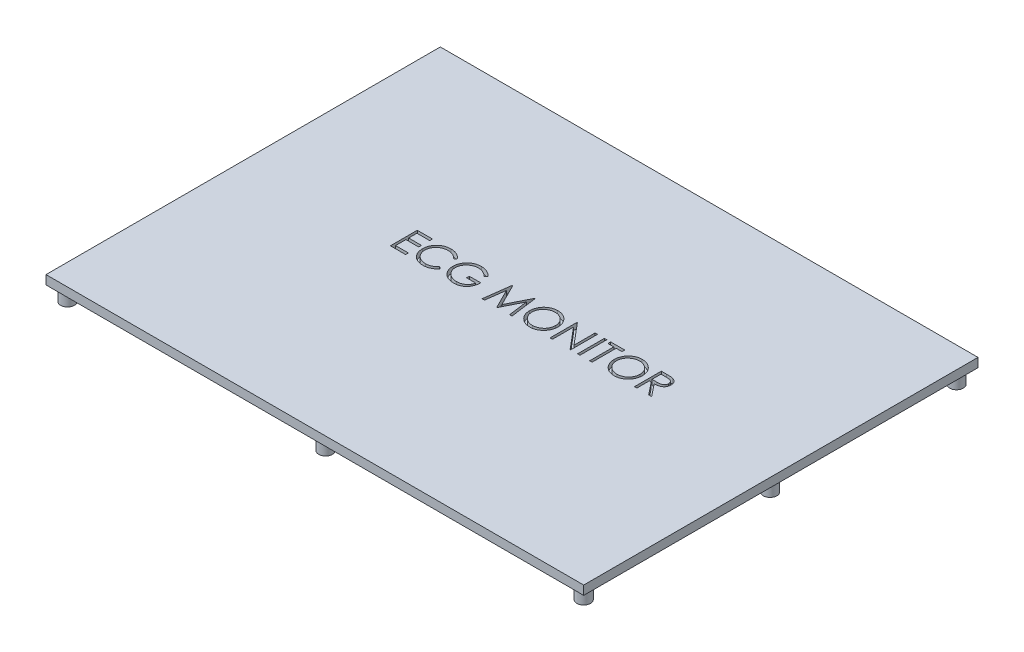
SolidWorks part; units mm, degrees
ref_plane "Front Plane" through (0, 0, 0) normal (0, 0, 1) x (1, 0, 0)
ref_plane "Top Plane" through (0, 0, 0) normal (0, 1, 0) x (1, 0, 0)
ref_plane "Right Plane" through (0, 0, 0) normal (1, 0, 0) x (0, 0, -1)
sketch "Sketch1" plane through (0, 0, 0) normal (0, 1, 0) x (1, 0, 0)
  line L1 (-75, 55) -> (75, 55)
  line L2 (-75, 55) -> (-75, -55)
  line L3 (-75, -55) -> (75, -55)
  line L4 (75, 55) -> (75, -55)
  line L5 (-75, 55) -> (75, -55) construction
  line L6 (-75, -55) -> (75, 55) construction
  point P0 (0, 0)
  dimension "D1" = 150
  dimension "D2" = 110
extrude "Boss-Extrude1" add sketch "Sketch1" along normal blind 2.5
sketch "Sketch2" plane through (0, 0, 0) normal (0, -1, 0) x (1, 0, 0)
  line L0 (-75, -55) -> (-75, 55) construction
  line L1 (-75, 55) -> (75, 55) construction
  line L2 (75, 55) -> (75, -55) construction
  line L3 (75, -55) -> (-75, -55) construction
  circle A0 centre (-72, 52) radius 1.9
  circle A1 centre (0, 52) radius 1.9
  circle A2 centre (72, 52) radius 1.9
  circle A3 centre (72, 0) radius 1.9
  circle A4 centre (72, -52) radius 1.9
  circle A5 centre (0, -52) radius 1.9
  circle A6 centre (-72, -52) radius 1.9
  circle A7 centre (-72, 0) radius 1.9
  point P18 (-75, 0)
  dimension "D1" = 3.8
  dimension "D4" = 3.8
  dimension "D8" = 3.8
  dimension "D12" = 3.8
  dimension "D14" = 3.8
  dimension "D18" = 3.8
  dimension "D19" = 3.8
  dimension "D23" = 3.8
  dimension "D2" = 3
  dimension "D3" = 55
  dimension "D5" = 3
  dimension "D6" = 3
  dimension "D7" = 3
  dimension "D9" = 75
  dimension "D10" = 3
  dimension "D11" = 3
  dimension "D13" = 3
  dimension "D15" = 55
  dimension "D16" = 3
  dimension "D17" = 3
  dimension "D20" = 3
  dimension "D21" = 75
  dimension "D22" = 3
  dimension "D24" = 3
extrude "Boss-Extrude2" add sketch "Sketch2" along normal blind 4
sketch "Sketch3" plane through (0, 2.5, 0) normal (0, 1, 0) x (1, 0, 0)
  line L0 (-34.8821, 0) -> (39.3846, 0) construction
  text T0 "ECG MONITOR" font "Century Gothic" height 7.5
extrude "Cut-Extrude1" cut sketch "Sketch3" against normal blind 1.5
